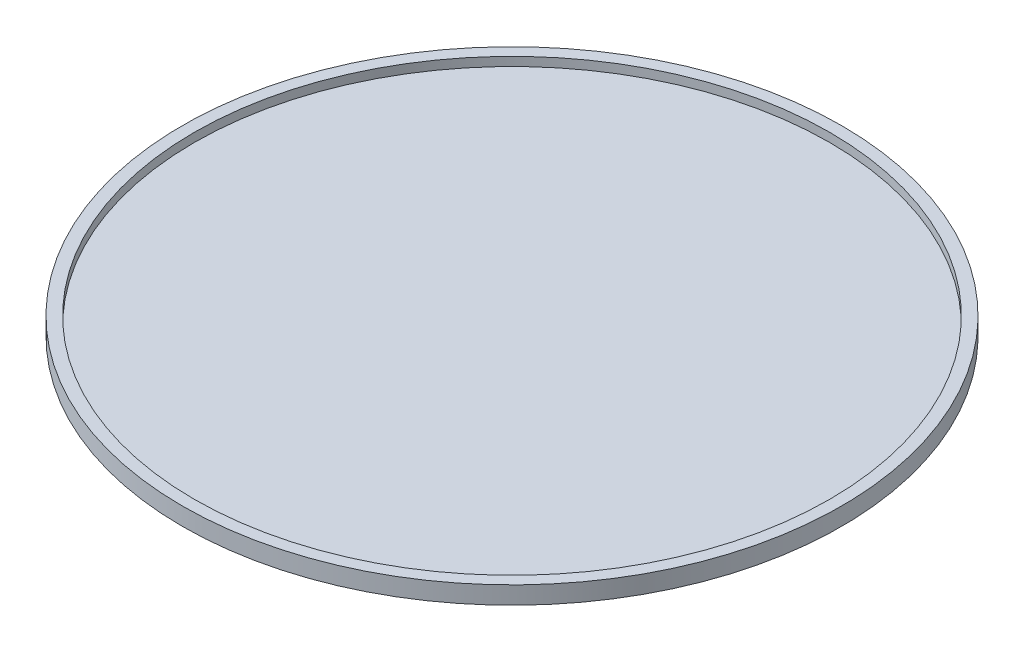
SolidWorks part; units mm, degrees
material "Thornel VCB-20 Carbon Cloth"
ref_plane "Front Plane" through (0, 0, 0) normal (0, 0, 1) x (1, 0, 0)
ref_plane "Top Plane" through (0, 0, 0) normal (0, 1, 0) x (1, 0, 0)
ref_plane "Right Plane" through (0, 0, 0) normal (1, 0, 0) x (0, 0, -1)
sketch "Sketch1" plane through (0, 0, 0) normal (0, 1, 0) x (1, 0, 0)
  circle A0 centre (0, 0) radius 28
extrude "Boss-Extrude1" add sketch "Sketch1" along normal blind 1.5 contours A0
sketch "Sketch3" plane through (0, 1.5, 0) normal (0, 1, 0) x (1, 0, 0)
  circle A0 centre (0, 0) radius 27
extrude "Cut-Extrude1" cut sketch "Sketch3" against normal blind 0.75 contours A0
sketch "Sketch4" plane through (0, 0.75, 0) normal (0, 1, 0) x (1, 0, 0)
  circle A0 centre (0, 0) radius 27
